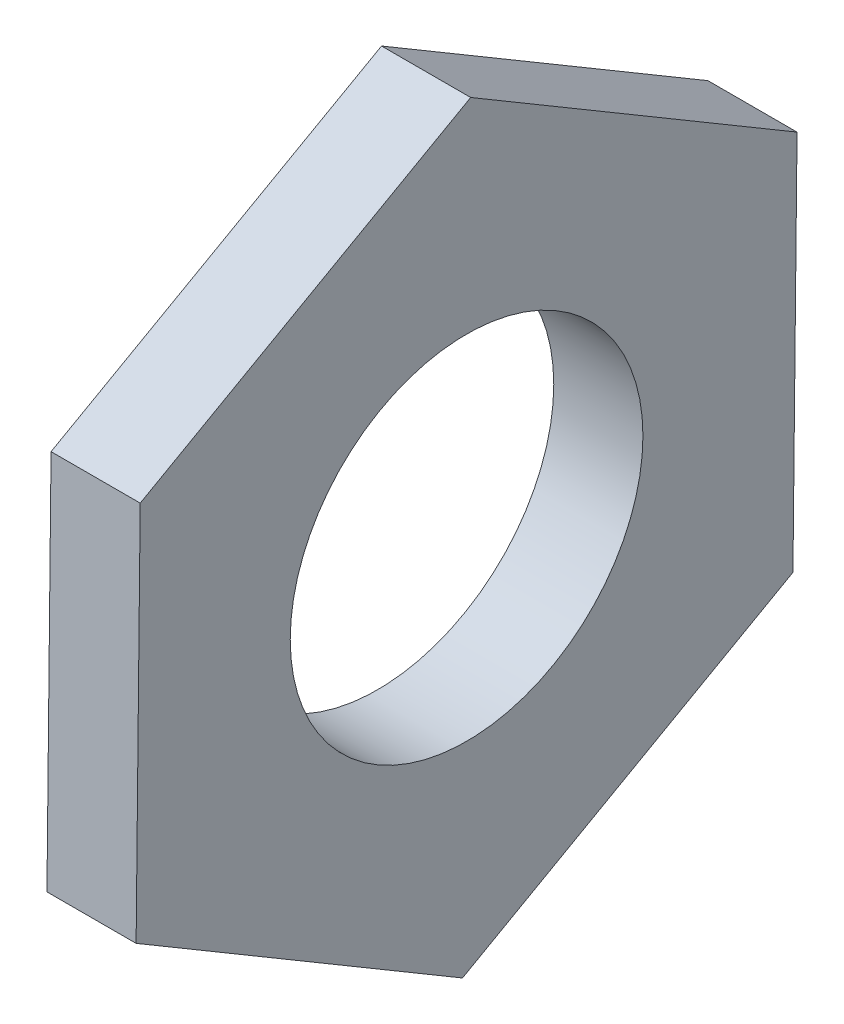
SolidWorks part; units mm, degrees
ref_plane "Front Plane" through (0, 0, 0) normal (0, 0, 1) x (1, 0, 0)
ref_plane "Top Plane" through (0, 0, 0) normal (0, 1, 0) x (1, 0, 0)
ref_plane "Right Plane" through (0, 0, 0) normal (1, 0, 0) x (0, 0, -1)
sketch "Sketch4" plane through (0, 0, 0) normal (1, 0, 0) x (0, 0, -1)
  line L1 (-47.0717, -26.5017) -> (-0.5847, -54.0162)
  line L2 (-0.5847, -54.0162) -> (46.487, -27.5144)
  line L3 (46.487, -27.5144) -> (47.0717, 26.5017)
  line L4 (47.0717, 26.5017) -> (0.5847, 54.0162)
  line L5 (0.5847, 54.0162) -> (-46.487, 27.5144)
  line L6 (-46.487, 27.5144) -> (-47.0717, -26.5017)
  circle A0 centre (0, 0) radius 46.7821 construction
extrude "Boss-Extrude1" add sketch "Sketch4" along normal blind 12.7
sketch "Sketch5" plane through (12.7, 0, 0) normal (1, 0, 0) x (0, 0, -1)
  circle A0 centre (0, 0) radius 25.1204
  point P3 (0, 0)
extrude "Cut-Extrude1" cut sketch "Sketch5" against normal through all both and the other way through all contours A0
